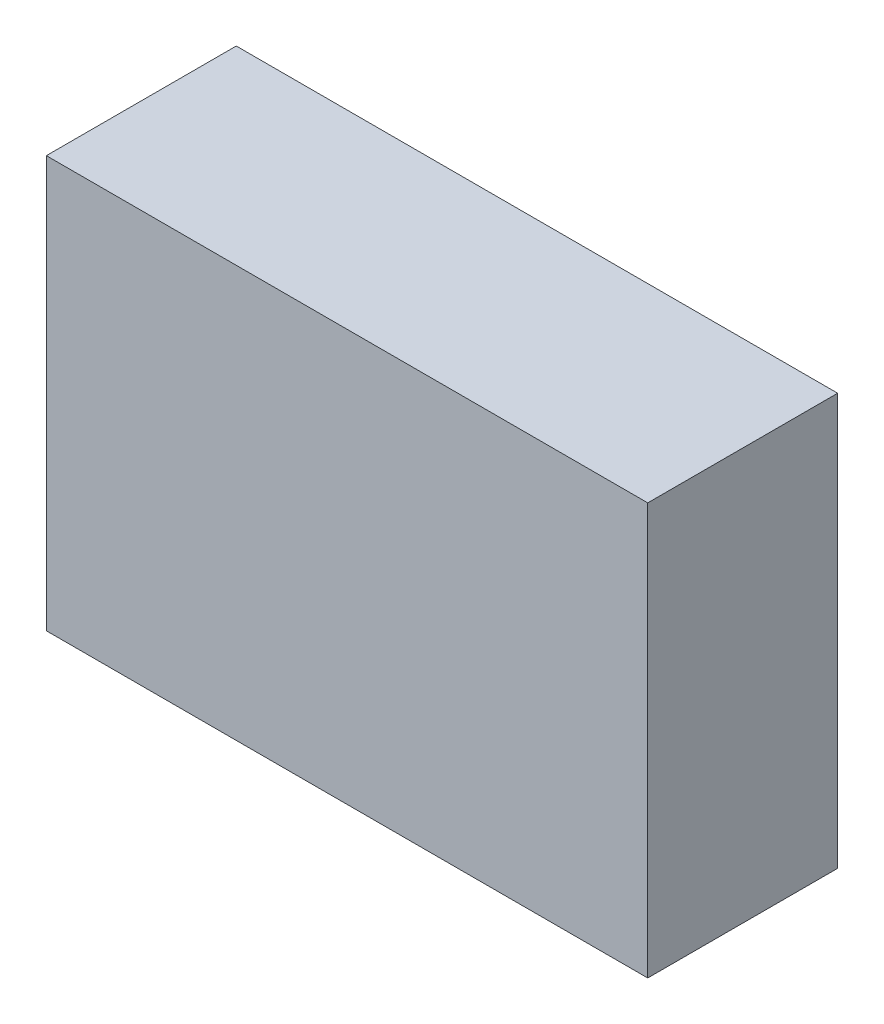
SolidWorks part; units mm, degrees
material "5052-H32"
ref_plane "Front Plane" through (0, 0, 0) normal (0, 0, 1) x (1, 0, 0)
ref_plane "Top Plane" through (0, 0, 0) normal (0, 1, 0) x (1, 0, 0)
ref_plane "Right Plane" through (0, 0, 0) normal (1, 0, 0) x (0, 0, -1)
sketch "Sketch1" plane through (0, 0, 0) normal (0, 0, 1) x (1, 0, 0)
  line L1 (0, 0) -> (950, 0)
  line L2 (0, 0) -> (0, 650)
  line L3 (0, 650) -> (950, 650)
  line L4 (950, 0) -> (950, 650)
  dimension "Length" = 950
  dimension "Width" = 650
extrude "Boss-Extrude1" add sketch "Sketch1" along normal blind 300
shell "Shell1" thickness 10
